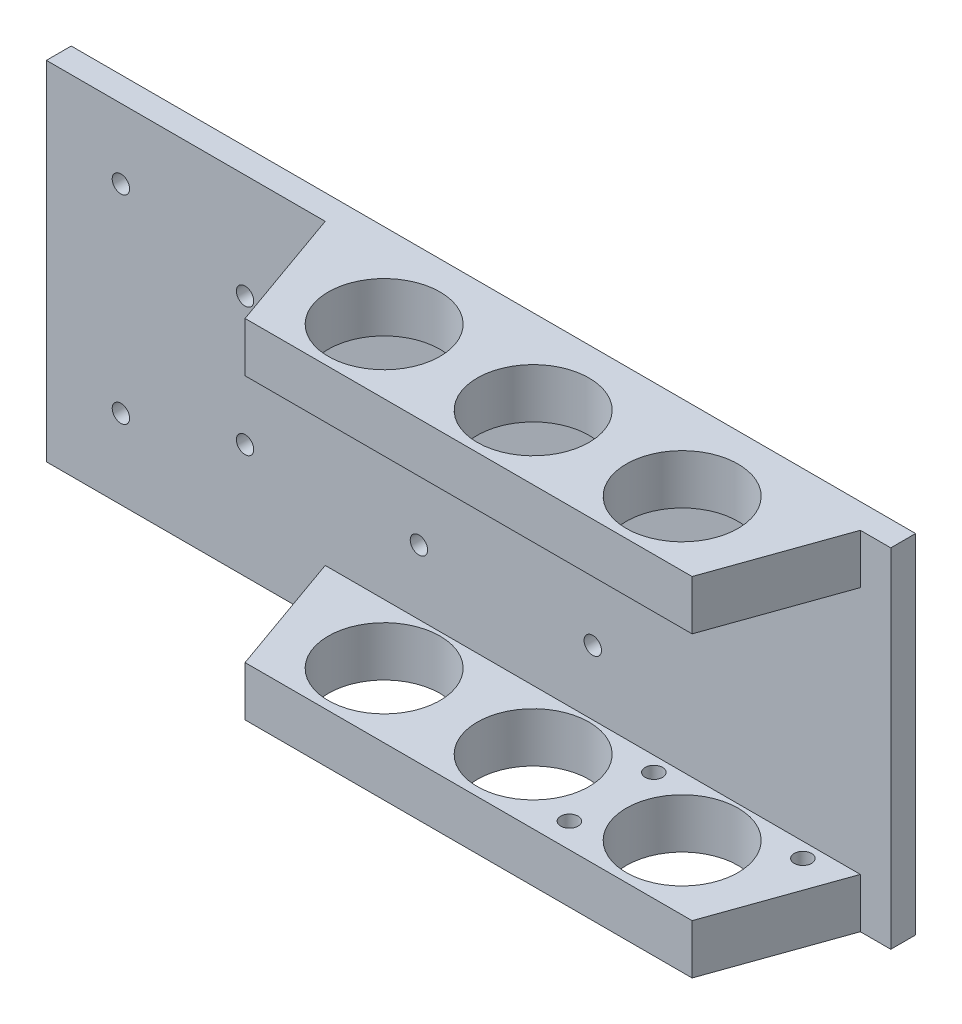
SolidWorks part; units mm, degrees
ref_plane "Спереди" through (0, 0, 0) normal (0, 0, 1) x (1, 0, 0)
ref_plane "Сверху" through (0, 0, 0) normal (0, 1, 0) x (1, 0, 0)
ref_plane "Справа" through (0, 0, 0) normal (1, 0, 0) x (0, 0, -1)
other "Configuration Table"
sketch "Эскиз1" plane through (0, 0, 0) normal (0, 1, 0) x (1, 0, 0)
  line L0 (0, 0) -> (0, -2.5) construction
  line L1 (-60, -2.5) -> (-53.8704, -2.5)
  line L2 (-60, -2.5) -> (-60, 2.5) construction
  line L3 (-60, 2.5) -> (60, 2.5)
  line L4 (60, -2.5) -> (60, 2.5)
  line L5 (-60, -2.5) -> (60, 2.5) construction
  line L6 (-60, 2.5) -> (60, -2.5) construction
  line L7 (0, 2.5) -> (0, -9.474) construction
  line L8 (0, -9.474) -> (0, -37.1338) construction
  line L9 (53.8704, -2.5) -> (45, -27.5)
  line L10 (45, -27.5) -> (-45, -27.5)
  line L11 (-53.8704, -2.5) -> (-45, -27.5)
  line L12 (-53.8704, -2.5) -> (0, -2.5) construction
  line L13 (53.8704, -2.5) -> (60, -2.5)
  line L14 (0, -2.5) -> (53.8704, -2.5) construction
  line L15 (-60, 2.5) -> (-80, 2.5)
  line L16 (-60, -2.5) -> (-80, -2.5)
  line L17 (-80, 2.5) -> (-80, -2.5)
  circle A0 centre (0, -14.5) radius 11.25
  circle A1 centre (30, -14.5) radius 11.25
  circle A2 centre (-30, -14.5) radius 11.25
  point P0 (0, 0)
  point P10 (0, -14.5)
  point P21 (0, -27.5)
  dimension "D4" = 22.5
  dimension "D10" = 20
  dimension "D1" = 120
  dimension "D2" = 5
  dimension "D3" = 12
  dimension "D6" = 250.464
  dimension "D7" = 25
  dimension "D8" = 30
  dimension "D9" = 90
  dimension "D5" = 2
extrude "Бобышка-Вытянуть1" add sketch "Эскиз1" along normal mid plane 70
sketch "Эскиз2" plane through (-80, 0, 0) normal (-1, 0, 0) x (0, 0, 1)
  line L0 (0, 0) -> (27.5, 0) construction
  line L1 (27.5, 35) -> (27.5, -35) construction
  line L2 (27.5, 0) -> (54.5347, 0) construction
  line L3 (2.5, -35) -> (27.5, -35) construction
  line L4 (2.5, 35) -> (27.5, 35) construction
  line L6 (2.5, -35) -> (27.5, -35) construction
  line L7 (2.5, 35) -> (27.5, 35) construction
  line L8 (27.5, 25) -> (27.5, -25)
  line L9 (2.5, 25) -> (2.5, -25)
  line L10 (2.5, 25) -> (27.5, 25)
  line L11 (27.5, 35) -> (27.5, 25) construction
  line L12 (2.5, 35) -> (2.5, 25) construction
  line L13 (2.5, -25) -> (27.5, -25)
  line L14 (2.5, -25) -> (2.5, -35) construction
  line L15 (27.5, -25) -> (27.5, -35) construction
  point P3 (2.5, 25)
  dimension "D1" = 10
extrude "Cut-Extrude1" cut sketch "Эскиз2" against normal through all
sketch "Sketch1" plane through (0, 0, -2.5) normal (0, 0, -1) x (-1, 0, 0)
  line L1 (80, 35) -> (110, 35)
  line L2 (80, 35) -> (80, -35)
  line L3 (80, -35) -> (110, -35)
  line L4 (-60, -35) -> (80, -35)
  line L5 (80, -35) -> (80, 35)
  line L6 (80, 35) -> (-60, 35)
  line L7 (-60, 35) -> (-60, -35)
  line L8 (-60, -35) -> (80, -35)
  line L10 (80, 35) -> (-60, 35)
  line L11 (-60, 35) -> (-60, -35)
  line L12 (110, 35) -> (110, -35)
  line L16 (80, -35) -> (80, 35)
  dimension "D2" = 30
  dimension "D1" = 0
extrude "Boss-Extrude1" add sketch "Sketch1" against normal blind 5
sketch "Sketch3" plane through (0, -35, 0) normal (0, -1, 0) x (1, 0, 0)
  line L0 (15.3, -2.5) -> (15.3, 27.5) construction
  line L1 (-45, 27.5) -> (45, 27.5) construction
  line L2 (60, -2.5) -> (-110, -2.5) construction
  line L3 (15.3, 5.5) -> (45.3, 5.5) construction
  circle A0 centre (45.3, 5.5) radius 1.75
  circle A10 centre (15.3, 22.5) radius 1.75
  circle A11 centre (15.3, 5.5) radius 1.75
  dimension "D1" = 8
  dimension "D2" = 5
  dimension "D6" = 3.5
  dimension "D7" = 3.5
  dimension "D4" = 3.5
  dimension "D3" = 15.3
  dimension "D5" = 30
extrude "Cut-Extrude4" cut sketch "Sketch3" against normal blind 10
sketch "Эскиз3" plane through (0, 0, -2.5) normal (0, 0, -1) x (-1, 0, 0)
  line L0 (110, -12) -> (-60, -12) construction
  line L1 (110, 35) -> (110, -35) construction
  line L2 (-60, 35) -> (-60, -35) construction
  line L3 (110, 13.91) -> (-60, 13.91) construction
  line L4 (-60, -35) -> (110, -35) construction
  line L5 (80, 10.91) -> (-10, 10.91) construction
  line L6 (80, 16.91) -> (-10, 16.91) construction
  line L7 (80, -15.0031) -> (-10, -15.0031) construction
  line L8 (35, -12) -> (35, 13.91) construction
  line L9 (70, 20.955) -> (110, 20.955) construction
  line L10 (70, -19.045) -> (110, -19.045) construction
  line L11 (87.5, 15.955) -> (102.5, 15.955) construction
  line L12 (87.5, 25.955) -> (102.5, 25.955) construction
  line L13 (102.5, -24.045) -> (87.5, -24.045) construction
  line L14 (-60, 35) -> (110, 35) construction
  line L15 (35, 0.955) -> (70, 0.955) construction
  line L16 (95, 20.955) -> (95, -19.045) construction
  circle A0 centre (0, -12) radius 1.75
  circle A1 centre (35, -12) radius 1.75
  circle A2 centre (70, -12) radius 1.75
  circle A3 centre (35, 13.91) radius 1.75
  circle A4 centre (70, 13.91) radius 1.75
  circle A5 centre (0, 13.91) radius 1.75
  circle A6 centre (95, 20.955) radius 1.75
  circle A7 centre (95, -19.045) radius 1.75
  dimension "D5" = 3.5
  dimension "D15" = 3.5
  dimension "D16" = 3.5
  dimension "D1" = 23
  dimension "D2" = 6
  dimension "D3" = 31.9131
  dimension "D4" = 25.91
  dimension "D6" = 60
  dimension "D9" = 35
  dimension "D10" = 20
  dimension "D11" = 20
  dimension "D12" = 10
  dimension "D13" = 50
  dimension "D14" = 70
  dimension "D17" = 25
  dimension "D7" = 3
  dimension "D8" = 2
extrude "Вырез-Вытянуть2" cut sketch "Эскиз3" against normal blind 10
